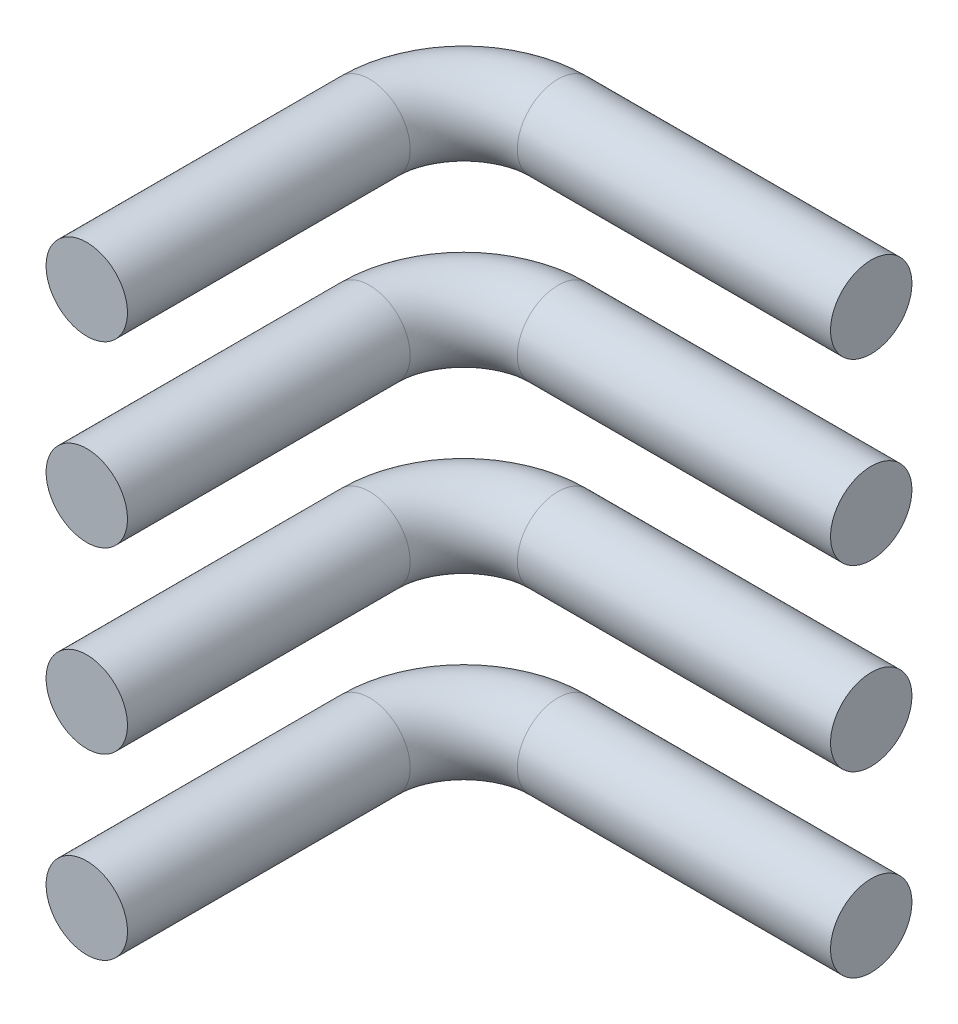
SolidWorks part; units mm, degrees
material "Silicon Rubber"
ref_plane "Front Plane" through (0, 0, 0) normal (0, 0, 1) x (1, 0, 0)
ref_plane "Top Plane" through (0, 0, 0) normal (0, 1, 0) x (1, 0, 0)
ref_plane "Right Plane" through (0, 0, 0) normal (1, 0, 0) x (0, 0, -1)
sketch "Sketch1" plane through (0, 0, 0) normal (0, 0, 1) x (1, 0, 0)
  line L0 (0, 23.247) -> (21.6166, 23.247)
  line L1 (0, 13.7728) -> (21.6167, 13.7728)
  line L2 (0, 4.2986) -> (21.6167, 4.2986)
  line L4 (0, -5.1756) -> (21.6167, -5.1756)
  dimension "D2" = 21.6166
  dimension "D1" = 4
sketch "Sketch2" plane through (0, 0, 0) normal (0, 1, 0) x (1, 0, 0)
  line L0 (21.6167, 0) -> (18.3667, 0)
  line L2 (18.3667, 0) -> (5, 0)
  line L3 (0, -5) -> (0, -20)
  arc A0 (5, 0) -> (0, -5) centre (5, -5) ccw
  point P10 (0, 0)
  dimension "D3" = 5
  dimension "D1" = 3.25
  dimension "D2" = 20
sketch "Sketch7" plane through (0, 0, 0) normal (0, 0, 1) x (1, 0, 0)
  line L0 (21.6166, 23.247) -> (0, 23.247)
curve "Curve3"
ref_plane "Plane1" through (21.6166, 23.247, 0) normal (1, 0, 0) x (0, 0, -1)
sketch "Sketch8" plane through (21.6166, 23.247, 0) normal (1, 0, 0) x (0, 0, -1)
  line L0 (-5, 0) -> (0, 0) construction
  circle A0 centre (0, 0) radius 2.159
  circle A1 centre (0, -9.4742) radius 2.159
  circle A2 centre (0, -28.4226) radius 2.159
  circle A3 centre (0, -18.9484) radius 2.159
  dimension "D1" = 4.318
  dimension "D2" = 4.318
  dimension "D3" = 4.318
  dimension "D4" = 4.318
sweep "Sweep1" add profiles "Sketch8" path "Curve3"
